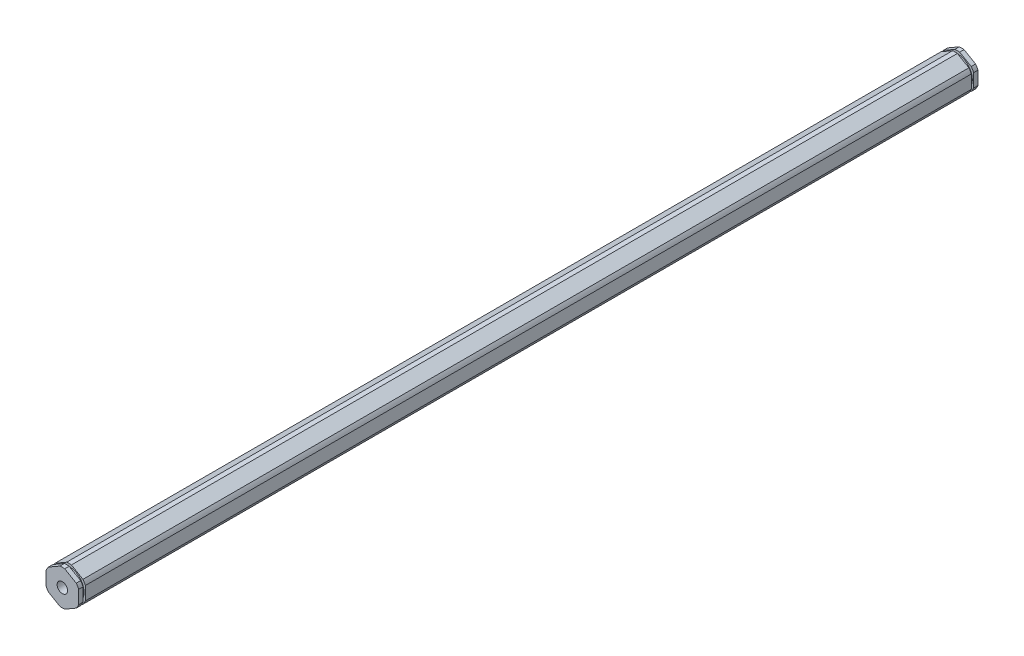
SolidWorks part; units mm, degrees
ref_plane "Front Plane" through (0, 0, 0) normal (0, 0, 1) x (1, 0, 0)
ref_plane "Top Plane" through (0, 0, 0) normal (0, 1, 0) x (1, 0, 0)
ref_plane "Right Plane" through (0, 0, 0) normal (1, 0, 0) x (0, 0, -1)
sketch "Sketch1" plane through (0, 0, 0) normal (0, 0, 1) x (1, 0, 0)
  line L1 (0, 7.3323) -> (-6.35, 3.6662)
  line L2 (-6.35, 3.6662) -> (-6.35, -3.6662)
  line L3 (-6.35, -3.6662) -> (0, -7.3323)
  line L4 (0, -7.3323) -> (6.35, -3.6662)
  line L5 (6.35, -3.6662) -> (6.35, 3.6662)
  line L6 (6.35, 3.6662) -> (0, 7.3323)
  circle A0 centre (0, 0) radius 6.35 construction
  circle A1 centre (0, 0) radius 6.858
  dimension "D1" = 12.7
  dimension "D2" = 13.716
extrude "Boss-Extrude1" add sketch "Sketch1" along normal mid plane 349.6945 contours L5 A1 L6 L1 L2 L3 L4
hole_wizard "#10-32 Tapped Hole1" positions "3DSketch1" profile "Sketch2" tap size "#10-32" standard "ANSI Inch"
sketch3d "3DSketch1"
  line L0 (0, 0, 174.8473) -> (0, 0, -174.8473) construction
  line L1 (0, 0, 174.8473) -> (0, 0, -174.8473) construction
  point P0 (0, 0, 174.8473)
  point P4 (0, 0, -174.8473)
sketch "Sketch2" plane through (0, 0, 174.8473) normal (1, 0, 0) x (0, -1, 0)
  line L0 (0, 0) -> (0, 17.5608)
  line L1 (0, 17.5608) -> (2.0193, 16.3474)
  line L2 (2.0193, 16.3474) -> (2.0193, 0)
  line L5 (2.0193, 0) -> (0, 0)
  line L10 (0, 17.5608) -> (-2.0193, 16.3474) construction
  line L11 (0, -6.35) -> (0, 107.95) construction
  dimension "Tap Drill Dia." = 4.0386
  dimension "Tap Drill Depth" = 16.3474
  dimension "Drill Angle" = 118
cosmetic thread "Hole Thread1" parameters "D1"=13.97, "D2"=4.826
cosmetic thread "Hole Thread2" parameters "D1"=13.97, "D2"=4.826
sketch "Sketch3" plane through (0, 0, 0) normal (1, 0, 0) x (0, 0, -1)
  line L0 (-175.1574, 0) -> (-171.1173, 0) construction
  line L1 (174.8472, 6.858) -> (-174.8473, 6.858) construction
  line L2 (-173.1328, 6.858) -> (-172.2438, 6.858)
  line L3 (-173.1328, 6.858) -> (-173.1328, 5.8547)
  line L4 (-173.1328, 5.8547) -> (-172.2438, 5.8547)
  line L5 (-172.2438, 6.858) -> (-172.2438, 5.8547)
  dimension "D1" = 0.889
  dimension "D2" = 5.8547
  dimension "D3" = 1.7145
revolve "Cut-Revolve1" cut sketch "Sketch3" angle 360 about L0
mirror "Mirror1" about plane through (0, 0, 0) normal (0, 0, 1) of "Cut-Revolve1"
